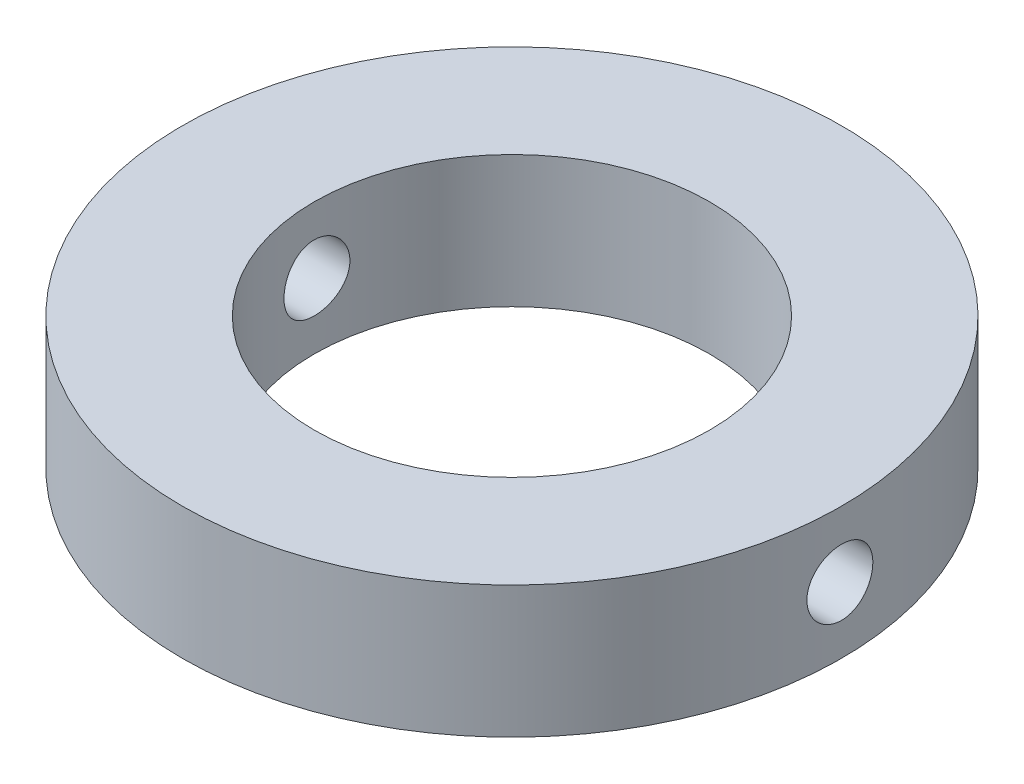
SolidWorks part; units mm, degrees
ref_plane "Front Plane" through (0, 0, 0) normal (0, 0, 1) x (1, 0, 0)
ref_plane "Top Plane" through (0, 0, 0) normal (0, 1, 0) x (1, 0, 0)
ref_plane "Right Plane" through (0, 0, 0) normal (1, 0, 0) x (0, 0, -1)
sketch "Sketch1" plane through (0, 0, 0) normal (0, 1, 0) x (1, 0, 0)
  circle A0 centre (0, 0) radius 25
  circle A1 centre (0, 0) radius 15
  dimension "D1" = 50
  dimension "D2" = 30
extrude "Boss-Extrude1" add sketch "Sketch1" along normal blind 10
sketch "Sketch2" plane through (0, 0, 0) normal (1, 0, 0) x (0, 0, -1)
  line L0 (15, 10) -> (-15, 10) construction
  circle A0 centre (0, 5) radius 2.5
  point P2 (0, 0)
  dimension "D1" = 5
  dimension "D2" = 5
extrude "Cut-Extrude1" cut sketch "Sketch2" against normal mid plane 60
